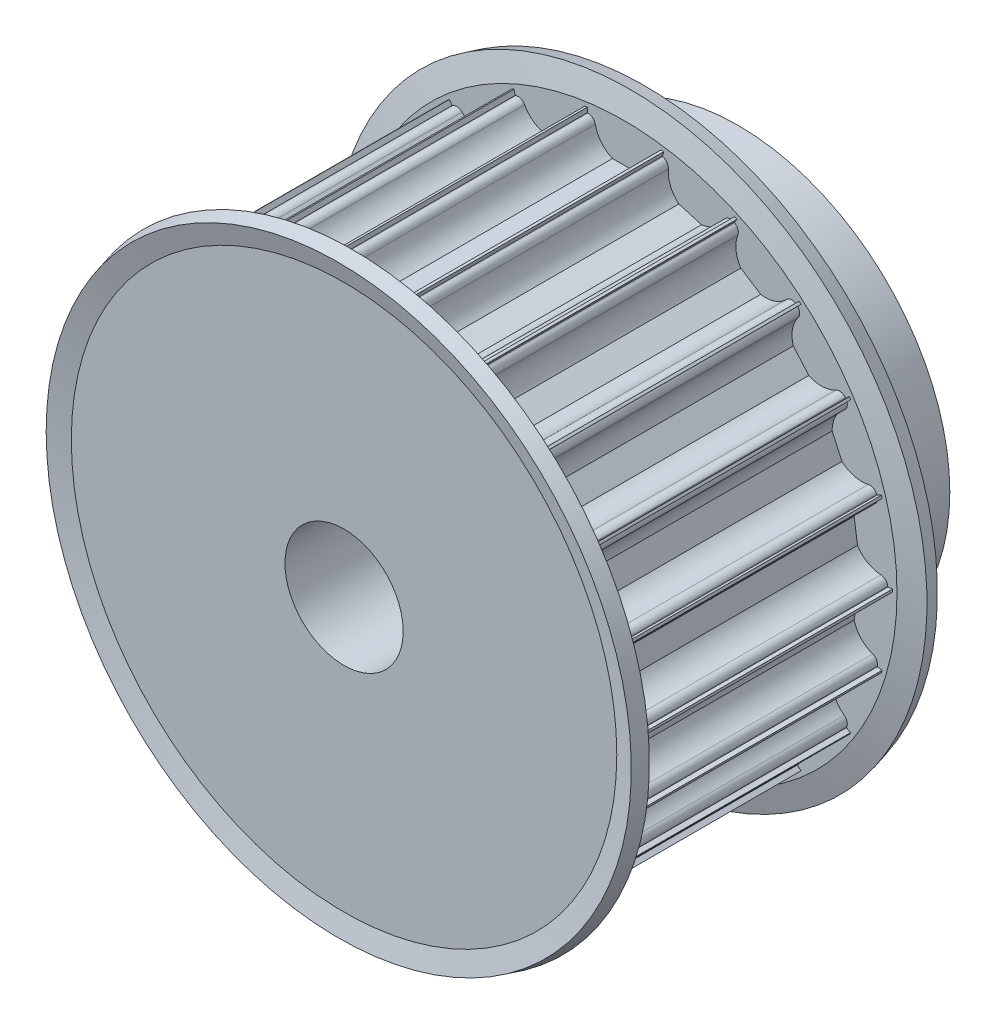
SolidWorks part; units mm, degrees
ref_plane "Front Plane" through (0, 0, 0) normal (0, 0, 1) x (1, 0, 0)
ref_plane "Top Plane" through (0, 0, 0) normal (0, 1, 0) x (1, 0, 0)
ref_plane "Right Plane" through (0, 0, 0) normal (1, 0, 0) x (0, 0, -1)
sketch "Sketch1" plane through (0, 0, 0) normal (1, 0, 0) x (0, 0, -1)
  line L0 (0, 0) -> (17.7994, 0) construction
  line L1 (0, 6) -> (40, 6)
  line L2 (40, 6) -> (40, 21.5)
  line L3 (40, 21.5) -> (30, 21.5)
  line L4 (30, 21.5) -> (30, 27.25)
  line L5 (30, 27.25) -> (0, 27.25)
  line L6 (0, 27.25) -> (0, 6)
  point P9 (0, 0)
  dimension "D1" = 6
  dimension "D2" = 27.25
  dimension "D3" = 15.5
  dimension "D4" = 30
  dimension "D5" = 40
revolve "Revolve1" add sketch "Sketch1" angle 360 about L0
sketch "Sketch2" plane through (0, 0, 0) normal (0, 0, 1) x (1, 0, 0)
  line L0 (-3.6742, 26.5) -> (-3.75, 26.5)
  line L1 (-3.75, 26.5) -> (-3.75, 28.5)
  line L2 (-3.75, 28.5) -> (3.75, 28.5)
  line L3 (3.75, 28.5) -> (3.75, 26.5)
  line L4 (3.75, 26.5) -> (3.6742, 26.5)
  line L5 (1.199, 23.75) -> (-1.199, 23.75)
  arc A0 (2.9394, 25.9) -> (1.199, 23.75) centre (0, 26.5) cw
  arc A1 (2.9394, 25.9) -> (3.6742, 26.5) centre (3.6742, 25.75) cw
  arc A2 (-2.9394, 25.9) -> (-3.6742, 26.5) centre (-3.6742, 25.75) ccw
  arc A3 (-1.199, 23.75) -> (-2.9394, 25.9) centre (0, 26.5) cw
  point P6 (0, 28.5)
  point P11 (3, 26.5)
  point P14 (-3, 26.5)
  dimension "D1" = 3
  dimension "D5" = 0.75
  dimension "D2" = 26.5
  dimension "D3" = 7.5
  dimension "D4" = 2
  dimension "D6" = 2.75
extrude "Cut-Extrude1" cut sketch "Sketch2" against normal up to next
pattern_circular "CirPattern1" count 22 over 360 about axis through (0, 0, 0) along (0, 0, 1) of "Cut-Extrude1"
sketch "Sketch3" plane through (0, 0, 0) normal (1, 0, 0) x (0, 0, -1)
  line L0 (15, 26.9539) -> (15, 10.9567) construction
  line L1 (30, 26.9539) -> (0, 26.9539) construction
  line L2 (30, 10.9567) -> (0, 10.9567) construction
  line L3 (30, 21.5) -> (30, 27.69)
  line L4 (30, 27.69) -> (30.5391, 29.7018)
  line L5 (30.5391, 29.7018) -> (29.0902, 30.09)
  line L6 (29.0902, 30.09) -> (28.4471, 27.69)
  line L7 (28.4471, 27.69) -> (28.4471, 21.5)
  line L8 (28.4471, 21.5) -> (30, 21.5)
  line L9 (40, 21.5) -> (30, 21.5) construction
  line L10 (1.5529, 27.69) -> (1.5529, 21.5)
  line L11 (0.9098, 30.09) -> (1.5529, 27.69)
  line L12 (-0.5391, 29.7018) -> (0.9098, 30.09)
  line L13 (0, 27.69) -> (-0.5391, 29.7018)
  line L14 (0, 21.5) -> (0, 27.69)
  line L15 (1.5529, 21.5) -> (0, 21.5)
  line L16 (0, 0) -> (-18.1407, 0) construction
  dimension "D1" = 15
  dimension "D2" = 6.19
  dimension "D3" = 1.5
  dimension "D4" = 2.4
revolve "Revolve4" add sketch "Sketch3" angle 360 about L16
